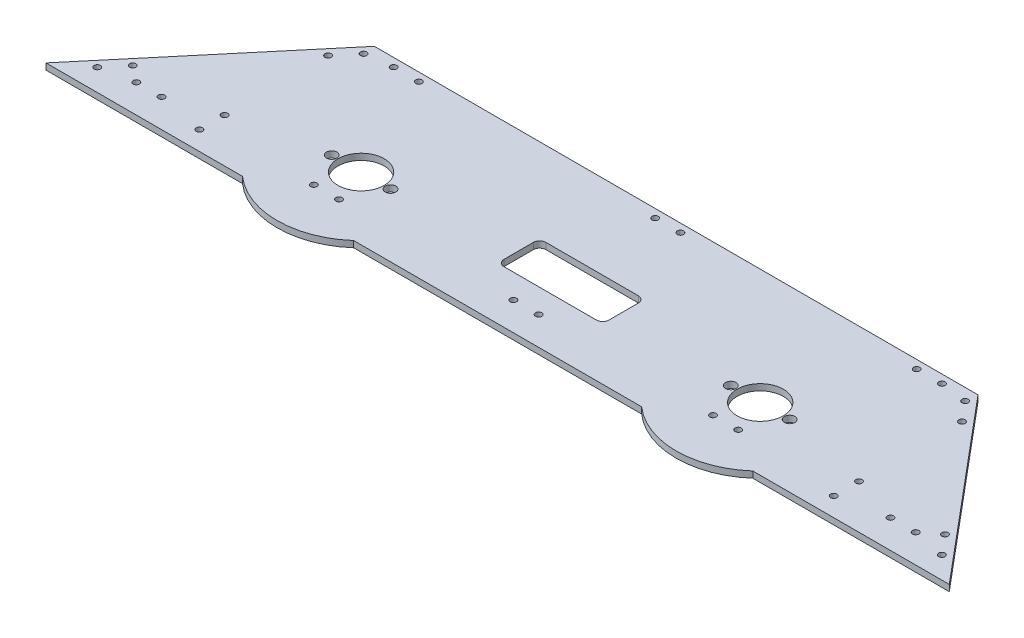
SolidWorks part; units mm, degrees
ref_plane "前视基准面" through (0, 0, 0) normal (0, 0, 1) x (1, 0, 0)
ref_plane "上视基准面" through (0, 0, 0) normal (0, 1, 0) x (1, 0, 0)
ref_plane "右视基准面" through (0, 0, 0) normal (1, 0, 0) x (0, 0, -1)
sketch "草图1" plane through (0, 0, 0) normal (0, 1, 0) x (1, 0, 0)
  line L0 (0, 0) -> (71.3235, 85)
  line L1 (0, 0) -> (93.5425, 0)
  line L2 (146.4575, 0) -> (283.5425, 0)
  line L3 (71.3235, 85) -> (358.6765, 85)
  line L4 (336.4575, 0) -> (430, 0)
  line L5 (215, 0) -> (215, 85) construction
  line L6 (430, 0) -> (358.6765, 85)
  circle A0 centre (120, 30) radius 11
  circle A1 centre (310, 30) radius 11
  arc A2 (93.5425, 0) -> (146.4575, 0) centre (120, 30) ccw
  arc A3 (336.4575, 0) -> (283.5425, 0) centre (310, 30) cw
  circle A4 centre (106, 30) radius 2.5
  circle A5 centre (134, 30) radius 2.5
  circle A6 centre (324, 30) radius 2.5
  circle A7 centre (296, 30) radius 2.5
  dimension "D4" = 22
  dimension "D7" = 80
  dimension "D10" = 5
  dimension "D1" = 430
  dimension "D2" = 85
  dimension "D3" = 130
  dimension "D5" = 30
  dimension "D6" = 95
  dimension "D8" = 28
  dimension "D9" = 14
extrude "凸台-拉伸1" add sketch "草图1" along normal blind 3
sketch "草图2" plane through (0, 3, 0) normal (0, 1, 0) x (1, 0, 0)
  line L0 (215, 85) -> (215, 0) construction
  line L1 (358.6765, 85) -> (71.3235, 85) construction
  line L2 (146.4575, 0) -> (283.5425, 0) construction
  line L3 (310, 30) -> (310, -23.3134) construction
  line L4 (336.4575, 0) -> (430, 0) construction
  line L5 (350.9344, 88.0038) -> (424.8659, -0.1043) construction
  line L6 (430, 0) -> (358.6765, 85) construction
  line L7 (358.6765, 85) -> (352.2719, 79.6259) construction
  circle A0 centre (221, 13.5) radius 1.5
  circle A1 centre (304, 13.5) radius 1.5
  circle A2 centre (316, 13.5) radius 1.5
  circle A3 centre (388.5, 13.5) radius 1.5
  circle A4 centre (400.5, 13.5) radius 1.5
  circle A5 centre (366, 9) radius 1.5
  circle A6 centre (366, 21) radius 1.5
  circle A7 centre (221, 81) radius 1.5
  circle A8 centre (333.5, 81) radius 1.5
  circle A9 centre (345.5, 81) radius 1.5
  circle A10 centre (358.1835, 79.3647) radius 1.5
  circle A11 centre (365.897, 70.1721) radius 1.5
  circle A12 centre (408.3209, 19.6132) radius 1.5
  circle A13 centre (416.0344, 10.4207) radius 1.5
  circle A14 centre (209, 81) radius 1.5
  circle A15 centre (96.5, 81) radius 1.5
  circle A16 centre (84.5, 81) radius 1.5
  circle A17 centre (71.8165, 79.3647) radius 1.5
  circle A18 centre (64.103, 70.1721) radius 1.5
  circle A19 centre (21.6791, 19.6132) radius 1.5
  circle A20 centre (13.9656, 10.4207) radius 1.5
  circle A21 centre (29.5, 13.5) radius 1.5
  circle A22 centre (41.5, 13.5) radius 1.5
  circle A23 centre (64, 21) radius 1.5
  circle A24 centre (64, 9) radius 1.5
  circle A25 centre (114, 13.5) radius 1.5
  circle A26 centre (126, 13.5) radius 1.5
  circle A27 centre (209, 13.5) radius 1.5
  dimension "D18" = 3
  dimension "D1" = 13.5
  dimension "D2" = 12
  dimension "D3" = 6
  dimension "D4" = 173.5
  dimension "D5" = 12
  dimension "D6" = 151
  dimension "D7" = 12
  dimension "D8" = 9
  dimension "D9" = 4
  dimension "D10" = 118.5
  dimension "D11" = 12
  dimension "D12" = 4
  dimension "D13" = 90
  dimension "D14" = 12
  dimension "D15" = 4
  dimension "D16" = 82
  dimension "D17" = 12
  dimension "D19" = 6
  dimension "D20" = 6
extrude "切除-拉伸2" cut sketch "草图2" against normal through all
sketch "草图3" plane through (0, 3, 0) normal (0, 1, 0) x (1, 0, 0)
  line L0 (215, 85) -> (215, 0) construction
  line L1 (358.6765, 85) -> (71.3235, 85) construction
  line L2 (146.4575, 0) -> (283.5425, 0) construction
  line L4 (190, 45) -> (240, 45)
  line L5 (190, 45) -> (190, 25)
  line L6 (190, 25) -> (240, 25)
  line L7 (240, 45) -> (240, 25)
  dimension "D1" = 50
  dimension "D2" = 25
  dimension "D3" = 20
  dimension "D4" = 25
extrude "切除-拉伸3" cut sketch "草图3" against normal through all
fillet "圆角1" radius 3 4 edges at (240, 1.5, -25) (240, 1.5, -45) (190, 1.5, -25) (190, 1.5, -45)
